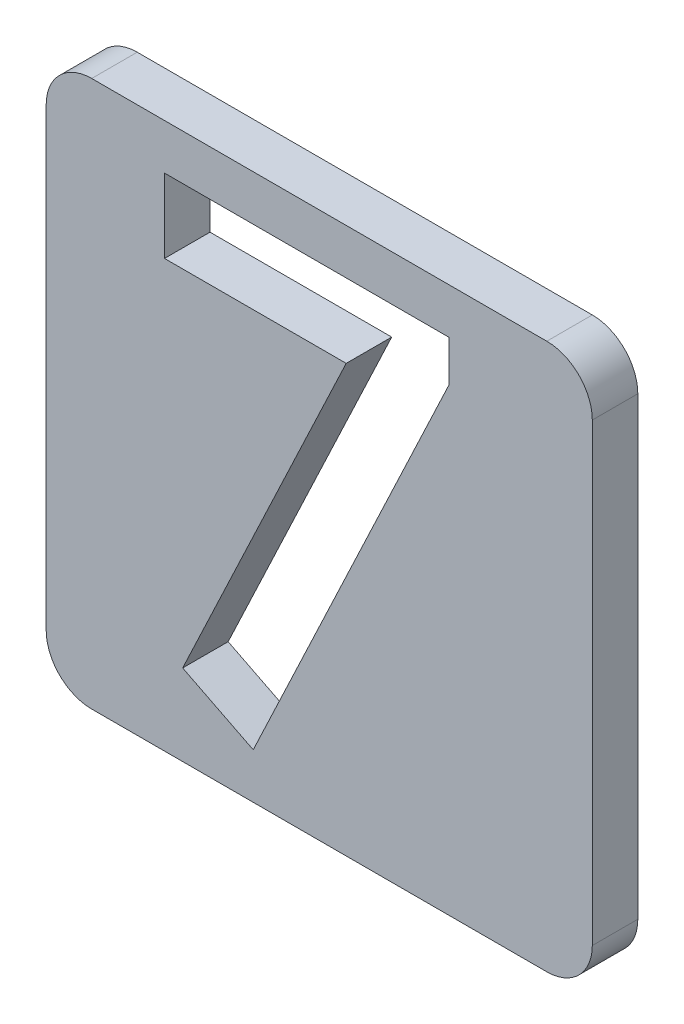
SolidWorks part; units mm, degrees
ref_plane "Front Plane" through (0, 0, 0) normal (0, 0, 1) x (1, 0, 0)
ref_plane "Top Plane" through (0, 0, 0) normal (0, 1, 0) x (1, 0, 0)
ref_plane "Right Plane" through (0, 0, 0) normal (1, 0, 0) x (0, 0, -1)
sketch "Sketch1" plane through (0, 0, 0) normal (0, 0, 1) x (1, 0, 0)
  line L1 (-50, 60) -> (50, 60)
  line L2 (-60, 50) -> (-60, -50)
  line L3 (-50, -60) -> (50, -60)
  line L4 (60, 50) -> (60, -50)
  line L5 (-60, 60) -> (60, -60) construction
  line L6 (-60, -60) -> (60, 60) construction
  arc A0 (-60, -50) -> (-50, -60) centre (-50, -50) ccw
  arc A1 (50, -60) -> (60, -50) centre (50, -50) ccw
  arc A2 (50, 60) -> (60, 50) centre (50, 50) cw
  arc A3 (-50, 60) -> (-60, 50) centre (-50, 50) ccw
  point P0 (0, 0)
  dimension "D3" = 10
  dimension "D1" = 120
  dimension "D2" = 120
extrude "Boss-Extrude1" add sketch "Sketch1" along normal blind 10 contours A3 L2 A0 L3 A1 L4 A2 L1
sketch "Sketch2" plane through (0, 0, 10) normal (0, 0, 1) x (1, 0, 0)
  line L0 (0, 0) -> (0, 40) construction
  line L1 (-50, 50) -> (50, 50) construction
  line L2 (-50, 50) -> (-50, -50) construction
  line L3 (-50, -50) -> (50, -50) construction
  line L4 (50, 50) -> (50, -50) construction
  line L5 (-50, 50) -> (50, -50) construction
  line L6 (-50, -50) -> (50, 50) construction
  line L7 (0, 40) -> (-40, 40) construction
  line L8 (-40, 40) -> (-40, 0) construction
  line L9 (-40, 0) -> (0, 0) construction
  line L11 (0, 20) -> (-20, 20) construction
  line L12 (-20, 40) -> (-20, 20) construction
  circle A0 centre (0, 40) radius 4 construction
  circle A1 centre (0, 20) radius 4 construction
  circle A2 centre (0, 0) radius 4 construction
  circle A3 centre (-20, 20) radius 4 construction
  circle A4 centre (-20, 40) radius 4 construction
  circle A5 centre (-40, 40) radius 4 construction
  circle A6 centre (0, 0) radius 4 construction
  circle A7 centre (20, 0) radius 4 construction
  circle A8 centre (40, 0) radius 4 construction
  circle A9 centre (40, 20) radius 4 construction
  circle A10 centre (40, 40) radius 4 construction
  circle A11 centre (20, 20) radius 4 construction
  circle A12 centre (0, 0) radius 4 construction
  circle A13 centre (0, -20) radius 4 construction
  circle A14 centre (0, -40) radius 4 construction
  circle A15 centre (20, -40) radius 4 construction
  circle A16 centre (40, -40) radius 4 construction
  circle A17 centre (20, -20) radius 4 construction
  circle A18 centre (0, 0) radius 4 construction
  circle A19 centre (-20, 0) radius 4 construction
  circle A20 centre (-40, 0) radius 4 construction
  circle A21 centre (-40, -20) radius 4 construction
  circle A22 centre (-40, -40) radius 4 construction
  circle A23 centre (-20, -20) radius 4 construction
  text T0 "7" font "Century Gothic" height 97.5
  point P0 (0, 0)
  point P55 (0, 0)
  dimension "D4" = 8
  dimension "D1" = 100
  dimension "D2" = 100
  dimension "D3" = 40
  dimension "D5" = 4
extrude "Cut-Extrude6" cut sketch "Sketch2" against normal blind 10
